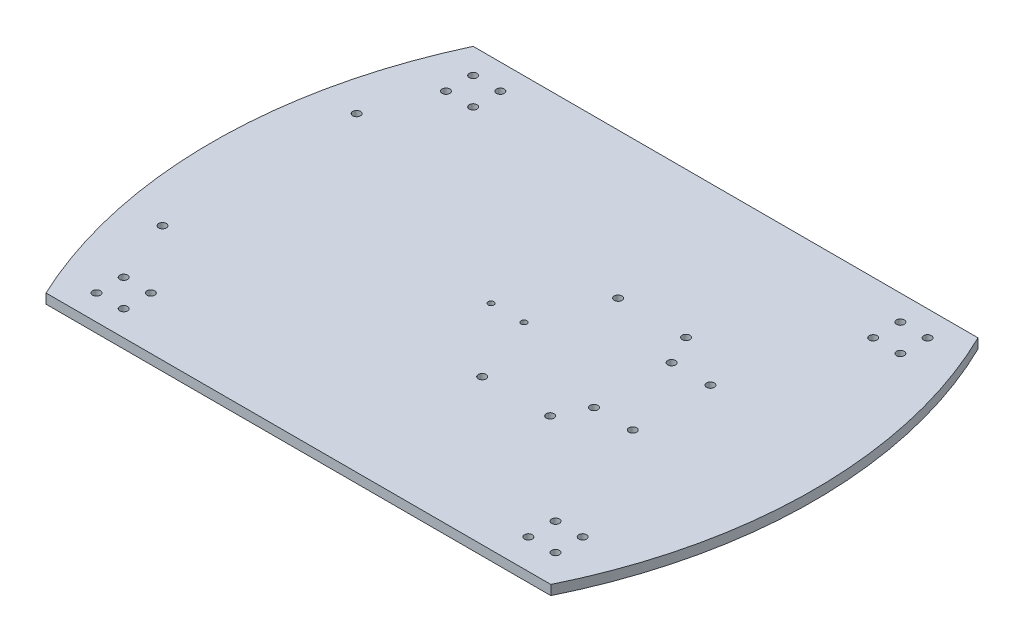
SolidWorks part; units mm, degrees
material "轻木"
ref_plane "前视基准面" through (0, 0, 0) normal (0, 0, 1) x (1, 0, 0)
ref_plane "上视基准面" through (0, 0, 0) normal (0, 1, 0) x (1, 0, 0)
ref_plane "右视基准面" through (0, 0, 0) normal (1, 0, 0) x (0, 0, -1)
sketch "草图1" plane through (0, 0, 0) normal (0, 1, 0) x (1, 0, 0)
  line L0 (-155.8847, 35) -> (154.1153, 35) construction
  line L1 (-131.3853, 145) -> (128.6147, 145)
  line L2 (-131.3853, 145) -> (-131.3853, -75)
  line L3 (-131.3853, -75) -> (128.6147, -75)
  line L4 (128.6147, 145) -> (128.6147, -75)
  line L5 (-131.3853, 118.4542) -> (-131.3853, 125) construction
  line L6 (-131.3853, 125) -> (128.6147, 125) construction
  line L7 (128.6147, 125) -> (128.6147, -55) construction
  line L8 (128.6147, -55) -> (-131.3853, -55) construction
  line L9 (-131.3853, -55) -> (-131.3853, 125) construction
  line L10 (-111.3853, -55) -> (-111.3853, 125) construction
  line L11 (-111.3853, 125) -> (108.6147, 125) construction
  line L12 (108.6147, 125) -> (108.6147, -55) construction
  line L13 (108.6147, -55) -> (-111.3853, -55) construction
  line L14 (-12.1933, 35) -> (4.8067, 35)
  line L15 (-118.3853, -62) -> (-104.3853, -62)
  line L16 (-118.3853, -62) -> (-118.3853, -48)
  line L17 (-118.3853, -48) -> (-104.3853, -48)
  line L18 (-104.3853, -62) -> (-104.3853, -48)
  line L19 (-118.3853, -62) -> (-104.3853, -48) construction
  line L20 (-118.3853, -48) -> (-104.3853, -62) construction
  line L21 (-118.3853, 132) -> (-104.3853, 132)
  line L22 (-118.3853, 132) -> (-118.3853, 118)
  line L23 (-118.3853, 118) -> (-104.3853, 118)
  line L24 (-104.3853, 132) -> (-104.3853, 118)
  line L25 (-118.3853, 132) -> (-104.3853, 118) construction
  line L26 (-118.3853, 118) -> (-104.3853, 132) construction
  line L27 (101.6147, -45.5856) -> (115.6147, -45.5856)
  line L28 (101.6147, -45.5856) -> (101.6147, -59.5856)
  line L29 (101.6147, -59.5856) -> (115.6147, -59.5856)
  line L30 (115.6147, -45.5856) -> (115.6147, -59.5856)
  line L31 (101.6147, -45.5856) -> (115.6147, -59.5856) construction
  line L32 (101.6147, -59.5856) -> (115.6147, -45.5856) construction
  line L33 (101.6147, 132) -> (115.6147, 132)
  line L34 (101.6147, 132) -> (101.6147, 118)
  line L35 (101.6147, 118) -> (115.6147, 118)
  line L36 (115.6147, 132) -> (115.6147, 118)
  line L37 (101.6147, 132) -> (115.6147, 118) construction
  line L38 (101.6147, 118) -> (115.6147, 132) construction
  line L39 (-131.3853, 35) -> (-131.3853, -15)
  line L40 (-131.3853, 35) -> (-131.3853, 85)
  line L41 (18.2563, 35) -> (18.2563, 70)
  line L42 (18.2563, 70) -> (53.2563, 70)
  line L43 (53.2563, 70) -> (53.2563, 0)
  line L44 (53.2563, 0) -> (18.2563, 0)
  line L45 (18.2563, 0) -> (18.2563, 35)
  line L46 (60.8159, 35) -> (60.8159, 55)
  line L47 (60.8159, 55) -> (80.8159, 55)
  line L48 (80.8159, 55) -> (80.8159, 15)
  line L49 (80.8159, 15) -> (60.8159, 15)
  line L50 (60.8159, 15) -> (60.8159, 35)
  arc A0 (-131.3853, 145) -> (-131.3853, -75) centre (103.3094, 35) ccw
  arc A1 (128.6147, 145) -> (128.6147, -75) centre (-95.8847, 35) cw
  circle A2 centre (-104.3853, 118) radius 2
  circle A3 centre (-118.3853, 132) radius 2
  circle A4 centre (-118.3853, 118) radius 2
  circle A5 centre (-104.3853, 132) radius 2
  circle A6 centre (101.6147, 132) radius 2
  circle A7 centre (101.6147, 118) radius 2
  circle A8 centre (115.6147, 118) radius 2
  circle A9 centre (115.6147, 132) radius 2
  circle A10 centre (115.6147, -45.5856) radius 2
  circle A11 centre (115.6147, -59.5856) radius 2
  circle A12 centre (101.6147, -59.5856) radius 2
  circle A13 centre (101.6147, -45.5856) radius 2
  circle A14 centre (-118.3853, -48) radius 2
  circle A15 centre (-118.3853, -62) radius 2
  circle A16 centre (-104.3853, -48) radius 2
  circle A17 centre (-104.3853, -62) radius 2
  circle A18 centre (-12.1933, 35) radius 1.5
  circle A19 centre (4.8067, 35) radius 1.5
  circle A20 centre (-131.3853, 85) radius 2
  circle A21 centre (-131.3853, -15) radius 2
  circle A22 centre (18.2563, 70) radius 2
  circle A23 centre (53.2563, 70) radius 2
  circle A24 centre (53.2563, 0) radius 2
  circle A25 centre (18.2563, 0) radius 2
  circle A26 centre (60.8159, 55) radius 2
  circle A27 centre (80.8159, 55) radius 2
  circle A28 centre (80.8159, 15) radius 2
  circle A29 centre (60.8159, 15) radius 2
  point P25 (108.6147, -52.5856)
  dimension "D1" = 220
  dimension "D16" = 4
  dimension "D17" = 17
  dimension "D18" = 3
  dimension "D19" = 50
  dimension "D21" = 70
  dimension "D24" = 20
  dimension "D2" = 260
  dimension "D3" = 310
  dimension "D4" = 20
  dimension "D5" = 20
  dimension "D6" = 20
  dimension "D7" = 20
  dimension "D8" = 14
  dimension "D9" = 14
  dimension "D10" = 14
  dimension "D11" = 14
  dimension "D12" = 14
  dimension "D13" = 14
  dimension "D14" = 14
  dimension "D15" = 14
  dimension "D20" = 50
  dimension "D22" = 35
  dimension "D23" = 35
  dimension "D25" = 40
  dimension "D26" = 20
extrude "凸台-拉伸2" add sketch "草图1" along normal blind 5
